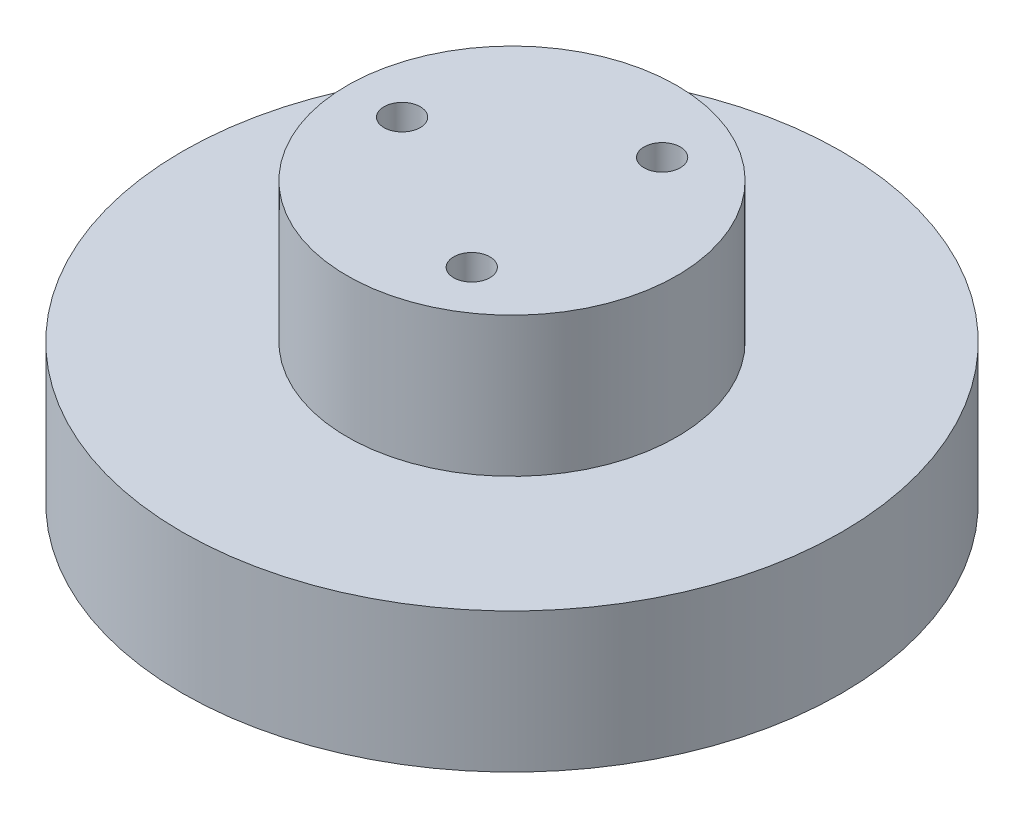
SolidWorks part; units mm, degrees
material "AISI 304"
ref_plane "Front Plane" through (0, 0, 0) normal (0, 0, 1) x (1, 0, 0)
ref_plane "Top Plane" through (0, 0, 0) normal (0, 1, 0) x (1, 0, 0)
ref_plane "Right Plane" through (0, 0, 0) normal (1, 0, 0) x (0, 0, -1)
sketch "Sketch1" plane through (0, 0, 0) normal (0, 0, 1) x (1, 0, 0)
  line L0 (0, 12.7) -> (-15, 12.7)
  line L1 (-15, 12.7) -> (-15, 0)
  line L2 (-15, 0) -> (-30, 0)
  line L3 (-30, 0) -> (-30, -12.7)
  line L4 (-30, -12.7) -> (0, -12.7)
  line L5 (0, -12.7) -> (0, 12.7)
  dimension "D1" = 12.7
  dimension "D2" = 30
  dimension "D3" = 15
revolve "Revolve1" add sketch "Sketch1" angle 360 about L5
sketch "Sketch2" plane through (0, 0, 0) normal (0, 0, 1) x (1, 0, 0)
  line L0 (-15, 12.7) -> (-15, 0) construction
  line L1 (-15, 9.525) -> (-2, 9.525)
  line L2 (-15, 9.525) -> (-15, 3.175)
  line L3 (-15, 3.175) -> (-2, 3.175)
  line L4 (-2, 9.525) -> (-2, 3.175)
  line L5 (15, 12.7) -> (-15, 12.7) construction
  line L6 (15, 0) -> (-15, 0) construction
  dimension "D1" = 3.175
  dimension "D2" = 3.175
  dimension "D3" = 2
extrude "Cut-Extrude1" [suppressed] cut sketch "Sketch2" against normal through all both and the other way through all
hole_wizard "M4x0.7 Tapped Hole1" positions "Sketch3" profile "Sketch4" tap size "M4x0.7" standard "ANSI Metric"
sketch "Sketch3" plane through (0, 12.7, 0) normal (0, 1, 0) x (1, 0, 0)
  line L0 (-10, 0) -> (0, 0) construction
  line L1 (0, 0) -> (5, 8.6603) construction
  line L3 (5, -8.6603) -> (0, 0) construction
  point P5 (5, 8.6603)
  point P7 (5, -8.6603)
  point P10 (-10, 0)
  dimension "D1" = 120
  dimension "D2" = 120
  dimension "D3" = 10
sketch "Sketch4" plane through (-10, 12.7, 0) normal (1, 0, 0) x (0, 0, 1)
  line L0 (0, 0) -> (0, 11.0914)
  line L1 (0, 11.0914) -> (1.65, 10.1)
  line L2 (1.65, 10.1) -> (1.65, 0)
  line L5 (1.65, 0) -> (0, 0)
  line L10 (0, 11.0914) -> (-1.65, 10.1) construction
  line L11 (0, -6.35) -> (0, 107.95) construction
  dimension "Tap Drill Dia." = 3.3
  dimension "Tap Drill Depth" = 10.1
  dimension "Drill Angle" = 118
cosmetic thread "Hole Thread1" parameters "D1"=8, "D2"=4
cosmetic thread "Hole Thread2" parameters "D1"=8, "D2"=4
cosmetic thread "Hole Thread6" parameters "D1"=8, "D2"=4
hole_wizard "M4x0.7 Tapped Hole2" positions "Sketch5" profile "Sketch6" tap size "M4x0.7" standard "ANSI Metric"
sketch "Sketch5" plane through (0, -12.7, 0) normal (0, -1, 0) x (-1, 0, 0)
  line L0 (-20, 0) -> (0, 0) construction
  line L1 (0, 0) -> (10, -17.3205) construction
  line L3 (0, 0) -> (10, 17.3205) construction
  point P1 (-20, 0)
  point P5 (10, -17.3205)
  point P10 (10, 17.3205)
  dimension "D1" = 120
  dimension "D2" = 120
  dimension "D3" = 20
sketch "Sketch6" plane through (20, -12.7, 0) normal (1, 0, 0) x (0, 0, -1)
  line L0 (0, 0) -> (0, 11.0914)
  line L1 (0, 11.0914) -> (1.65, 10.1)
  line L2 (1.65, 10.1) -> (1.65, 0)
  line L5 (1.65, 0) -> (0, 0)
  line L10 (0, 11.0914) -> (-1.65, 10.1) construction
  line L11 (0, -6.35) -> (0, 107.95) construction
  dimension "Tap Drill Dia." = 3.3
  dimension "Tap Drill Depth" = 10.1
  dimension "Drill Angle" = 118
cosmetic thread "Hole Thread3" parameters "D1"=8, "D2"=4
cosmetic thread "Hole Thread4" parameters "D1"=8, "D2"=4
cosmetic thread "Hole Thread5" parameters "D1"=8, "D2"=4
